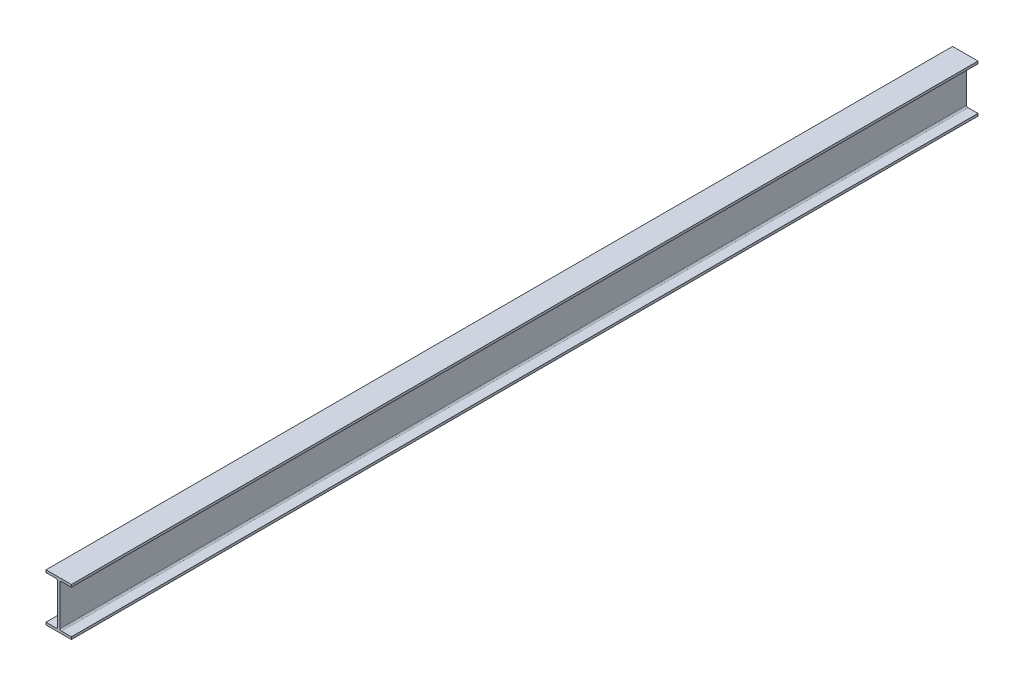
SolidWorks part; units mm, degrees
ref_plane "Front Plane" through (0, 0, 0) normal (0, 0, 1) x (1, 0, 0)
ref_plane "Top Plane" through (0, 0, 0) normal (0, 1, 0) x (1, 0, 0)
ref_plane "Right Plane" through (0, 0, 0) normal (1, 0, 0) x (0, 0, -1)
sketch "Sketch1" plane through (0, 0, 0) normal (0, 0, 1) x (1, 0, 0)
  line L0 (-4, -66) -> (-4, 66)
  line L1 (-9, 71) -> (-42, 71)
  line L2 (-42, 71) -> (-42, 79)
  line L3 (-42, 79) -> (42, 79)
  line L4 (42, 79) -> (42, 71)
  line L5 (42, 71) -> (9, 71)
  line L6 (4, 66) -> (4, -66)
  line L8 (-15.1309, 0) -> (0, 0) construction
  line L9 (42, -71) -> (9, -71)
  line L10 (42, -79) -> (42, -71)
  line L11 (-42, -79) -> (42, -79)
  line L12 (-42, -71) -> (-42, -79)
  line L13 (-9, -71) -> (-42, -71)
  arc A0 (-9, -71) -> (-4, -66) centre (-9, -66) ccw
  arc A1 (9, -71) -> (4, -66) centre (9, -66) cw
  arc A2 (9, 71) -> (4, 66) centre (9, 66) ccw
  arc A3 (-4, 66) -> (-9, 71) centre (-9, 66) ccw
  point P17 (-4, -71)
  point P20 (4, -71)
  point P23 (4, 71)
  point P26 (-4, 71)
  dimension "D7" = 5
  dimension "D1" = 142
  dimension "D2" = 8
  dimension "D3" = 84
  dimension "D4" = 38
  dimension "D5" = 8
  dimension "D6" = 4
extrude "Boss-Extrude1" add sketch "Sketch1" along normal blind 3000
